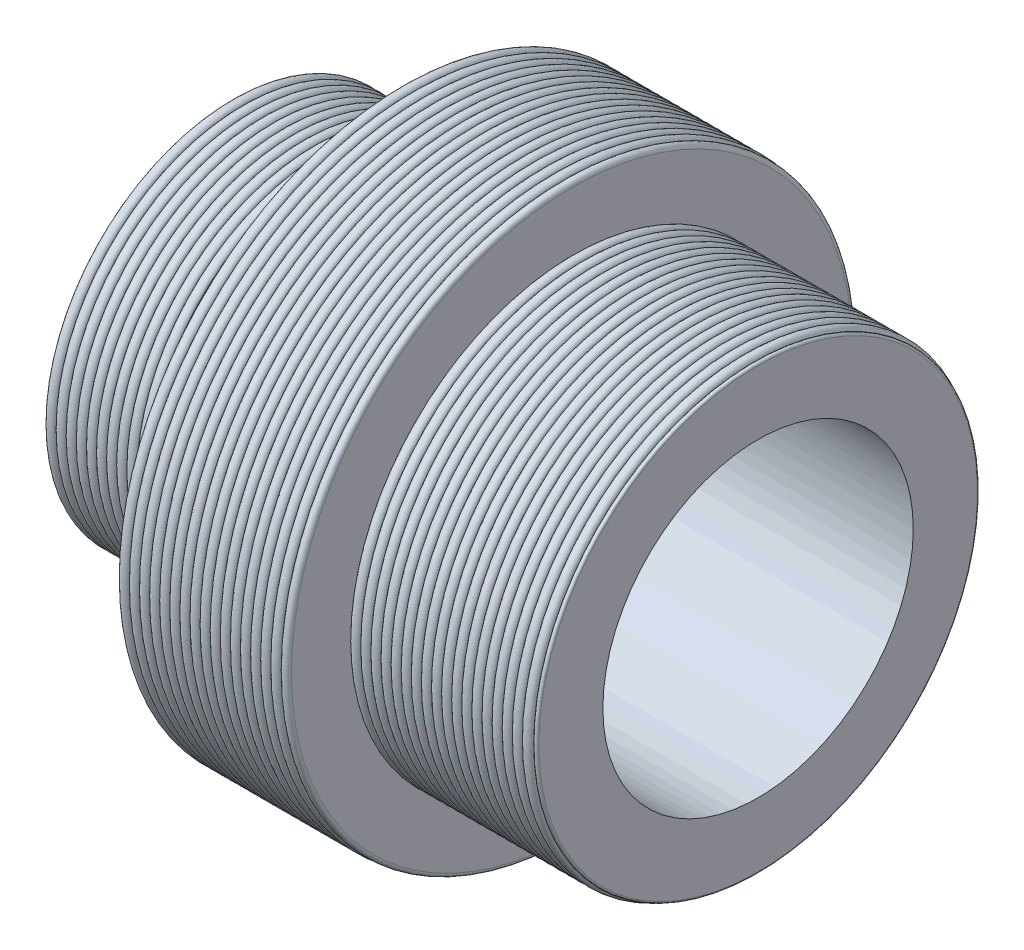
SolidWorks part; units mm, degrees
ref_plane "Alzado" through (0, 0, 0) normal (0, 0, 1) x (1, 0, 0)
ref_plane "Planta" through (0, 0, 0) normal (0, 1, 0) x (1, 0, 0)
ref_plane "Vista lateral" through (0, 0, 0) normal (1, 0, 0) x (0, 0, -1)
sketch "Croquis1" plane through (0, 0, 0) normal (0, 0, 1) x (1, 0, 0)
  line L0 (-55, 0) -> (55, 0) construction
  line L1 (0, 0) -> (0, 29.195) construction
  line L2 (48, 29.195) -> (13, 29.195)
  line L4 (13, 29.195) -> (-19, 29.195)
  line L5 (-19, 29.195) -> (-51, 29.195)
  line L6 (13, 29.195) -> (13, 52.78)
  line L7 (48, 29.195) -> (48, 41.245)
  line L8 (-19, 29.195) -> (-19, 52.78)
  line L9 (-51, 29.195) -> (-51, 34.565)
  line L11 (-51, 34.565) -> (-19, 34.565) construction
  line L12 (-19, 52.78) -> (13, 52.78) construction
  line L13 (13, 41.245) -> (48, 41.245) construction
  arc A0 (-51, 34.565) -> (-49.1, 34.565) centre (-50.05, 34.565) cw
  arc A1 (-49.1, 34.565) -> (-47.2, 34.565) centre (-48.15, 34.565) cw
  arc A2 (-47.2, 34.565) -> (-45.3, 34.565) centre (-46.25, 34.565) cw
  arc A3 (-45.3, 34.565) -> (-43.4, 34.565) centre (-44.35, 34.565) cw
  arc A4 (-43.4, 34.565) -> (-41.5, 34.565) centre (-42.45, 34.565) cw
  arc A5 (-41.5, 34.565) -> (-39.6, 34.565) centre (-40.55, 34.565) cw
  arc A6 (-39.6, 34.565) -> (-37.7, 34.565) centre (-38.65, 34.565) cw
  arc A7 (-37.7, 34.565) -> (-35.8, 34.565) centre (-36.75, 34.565) cw
  arc A8 (-35.8, 34.565) -> (-33.9, 34.565) centre (-34.85, 34.565) cw
  arc A9 (-33.9, 34.565) -> (-32, 34.565) centre (-32.95, 34.565) cw
  arc A10 (-32, 34.565) -> (-30.1, 34.565) centre (-31.05, 34.565) cw
  arc A11 (-30.1, 34.565) -> (-28.2, 34.565) centre (-29.15, 34.565) cw
  arc A12 (-28.2, 34.565) -> (-26.3, 34.565) centre (-27.25, 34.565) cw
  arc A13 (-26.3, 34.565) -> (-24.4, 34.565) centre (-25.35, 34.565) cw
  arc A14 (-24.4, 34.565) -> (-22.5, 34.565) centre (-23.45, 34.565) cw
  arc A15 (-22.5, 34.565) -> (-20.6, 34.565) centre (-21.55, 34.565) cw
  arc A16 (-20.6, 34.565) -> (-19, 34.565) centre (-19.8, 34.565) cw
  arc A17 (-19, 52.78) -> (-17.1, 52.78) centre (-18.05, 52.78) cw
  arc A18 (-17.1, 52.78) -> (-15.2, 52.78) centre (-16.15, 52.78) cw
  arc A19 (-15.2, 52.78) -> (-13.3, 52.78) centre (-14.25, 52.78) cw
  arc A20 (-13.3, 52.78) -> (-11.4, 52.78) centre (-12.35, 52.78) cw
  arc A21 (-11.4, 52.78) -> (-9.5, 52.78) centre (-10.45, 52.78) cw
  arc A22 (-9.5, 52.78) -> (-7.6, 52.78) centre (-8.55, 52.78) cw
  arc A23 (-7.6, 52.78) -> (-5.7, 52.78) centre (-6.65, 52.78) cw
  arc A24 (-5.7, 52.78) -> (-3.8, 52.78) centre (-4.75, 52.78) cw
  arc A25 (-3.8, 52.78) -> (-1.9, 52.78) centre (-2.85, 52.78) cw
  arc A26 (-1.9, 52.78) -> (0, 52.78) centre (-0.95, 52.78) cw
  arc A27 (0, 52.78) -> (1.9, 52.78) centre (0.95, 52.78) cw
  arc A28 (1.9, 52.78) -> (3.8, 52.78) centre (2.85, 52.78) cw
  arc A29 (3.8, 52.78) -> (5.7, 52.78) centre (4.75, 52.78) cw
  arc A30 (5.7, 52.78) -> (7.6, 52.78) centre (6.65, 52.78) cw
  arc A31 (7.6, 52.78) -> (9.5, 52.78) centre (8.55, 52.78) cw
  arc A32 (9.5, 52.78) -> (11.4, 52.78) centre (10.45, 52.78) cw
  arc A33 (11.4, 52.78) -> (13, 52.78) centre (12.2, 52.78) cw
  arc A34 (13, 41.245) -> (14.9, 41.245) centre (13.95, 41.245) cw
  arc A35 (14.9, 41.245) -> (16.8, 41.245) centre (15.85, 41.245) cw
  arc A36 (16.8, 41.245) -> (18.7, 41.245) centre (17.75, 41.245) cw
  arc A37 (18.7, 41.245) -> (20.6, 41.245) centre (19.65, 41.245) cw
  arc A38 (20.6, 41.245) -> (22.5, 41.245) centre (21.55, 41.245) cw
  arc A39 (22.5, 41.245) -> (24.4, 41.245) centre (23.45, 41.245) cw
  arc A40 (24.4, 41.245) -> (26.3, 41.245) centre (25.35, 41.245) cw
  arc A41 (26.3, 41.245) -> (28.2, 41.245) centre (27.25, 41.245) cw
  arc A42 (28.2, 41.245) -> (30.1, 41.245) centre (29.15, 41.245) cw
  arc A43 (30.1, 41.245) -> (32, 41.245) centre (31.05, 41.245) cw
  arc A44 (32, 41.245) -> (33.9, 41.245) centre (32.95, 41.245) cw
  arc A45 (33.9, 41.245) -> (35.8, 41.245) centre (34.85, 41.245) cw
  arc A46 (35.8, 41.245) -> (37.7, 41.245) centre (36.75, 41.245) cw
  arc A47 (37.7, 41.245) -> (39.6, 41.245) centre (38.65, 41.245) cw
  arc A48 (39.6, 41.245) -> (41.5, 41.245) centre (40.55, 41.245) cw
  arc A49 (41.5, 41.245) -> (43.4, 41.245) centre (42.45, 41.245) cw
  arc A50 (43.4, 41.245) -> (45.3, 41.245) centre (44.35, 41.245) cw
  arc A51 (45.3, 41.245) -> (47.2, 41.245) centre (46.25, 41.245) cw
  arc A52 (47.2, 41.245) -> (48, 41.245) centre (47.6, 41.245) cw
  point P4 (-48.15, 34.565)
  point P18 (-47.2, 34.565)
  point P19 (-46.25, 34.565)
  point P20 (-45.3, 34.565)
  point P21 (-44.35, 34.565)
  point P22 (-43.4, 34.565)
  point P23 (-42.45, 34.565)
  point P24 (-41.5, 34.565)
  point P25 (-40.55, 34.565)
  point P26 (-39.6, 34.565)
  point P27 (-38.65, 34.565)
  point P28 (-37.7, 34.565)
  point P29 (-36.75, 34.565)
  point P30 (-35.8, 34.565)
  point P31 (-34.85, 34.565)
  point P32 (-33.9, 34.565)
  point P33 (-32.95, 34.565)
  point P34 (-32, 34.565)
  point P35 (-31.05, 34.565)
  point P36 (-30.1, 34.565)
  point P37 (-29.15, 34.565)
  point P38 (-28.2, 34.565)
  point P39 (-27.25, 34.565)
  point P40 (-26.3, 34.565)
  point P41 (-25.35, 34.565)
  point P42 (-24.4, 34.565)
  point P43 (-23.45, 34.565)
  point P44 (-22.5, 34.565)
  point P45 (-21.55, 34.565)
  point P46 (-20.6, 34.565)
  point P47 (-19.8, 34.565)
  point P80 (-18.05, 52.78)
  point P81 (-17.1, 52.78)
  point P82 (-16.15, 52.78)
  point P83 (-15.2, 52.78)
  point P84 (-14.25, 52.78)
  point P85 (-13.3, 52.78)
  point P86 (-12.35, 52.78)
  point P87 (-11.4, 52.78)
  point P88 (-10.45, 52.78)
  point P89 (-9.5, 52.78)
  point P90 (-8.55, 52.78)
  point P91 (-7.6, 52.78)
  point P92 (-6.65, 52.78)
  point P93 (-5.7, 52.78)
  point P94 (-4.75, 52.78)
  point P95 (-3.8, 52.78)
  point P96 (-2.85, 52.78)
  point P97 (-1.9, 52.78)
  point P98 (-0.95, 52.78)
  point P99 (0, 52.78)
  point P100 (0.95, 52.78)
  point P101 (1.9, 52.78)
  point P102 (2.85, 52.78)
  point P103 (3.8, 52.78)
  point P104 (4.75, 52.78)
  point P105 (5.7, 52.78)
  point P106 (6.65, 52.78)
  point P107 (7.6, 52.78)
  point P108 (8.55, 52.78)
  point P109 (9.5, 52.78)
  point P110 (10.45, 52.78)
  point P111 (11.4, 52.78)
  point P112 (12.2, 52.78)
  point P147 (13.95, 41.245)
  point P148 (14.9, 41.245)
  point P149 (15.85, 41.245)
  point P150 (16.8, 41.245)
  point P151 (17.75, 41.245)
  point P152 (18.7, 41.245)
  point P153 (19.65, 41.245)
  point P154 (20.6, 41.245)
  point P155 (21.55, 41.245)
  point P156 (22.5, 41.245)
  point P157 (23.45, 41.245)
  point P158 (24.4, 41.245)
  point P159 (25.35, 41.245)
  point P160 (26.3, 41.245)
  point P161 (27.25, 41.245)
  point P162 (28.2, 41.245)
  point P163 (29.15, 41.245)
  point P164 (30.1, 41.245)
  point P166 (31.05, 41.245)
  point P167 (32, 41.245)
  point P168 (32.95, 41.245)
  point P169 (33.9, 41.245)
  point P171 (34.85, 41.245)
  point P172 (35.8, 41.245)
  point P174 (36.75, 41.245)
  point P175 (37.7, 41.245)
  point P177 (38.65, 41.245)
  point P178 (39.6, 41.245)
  point P179 (40.55, 41.245)
  point P181 (41.5, 41.245)
  point P183 (42.45, 41.245)
  point P184 (43.4, 41.245)
  point P185 (47.6, 41.245)
  point P186 (44.35, 41.245)
  point P187 (45.3, 41.245)
  point P188 (46.25, 41.245)
  point P190 (47.2, 41.245)
  dimension "D1" = 35
  dimension "D2" = 29.195
  dimension "D3" = 23.585
  dimension "D4" = 5.37
  dimension "D5" = 32
  dimension "D6" = 32
  dimension "D7" = 0.95
  dimension "D8" = 12.05
  dimension "D9" = 0.95
  dimension "D10" = 0.95
  dimension "D11" = 0.95
  dimension "D12" = 0.95
  dimension "D13" = 0.95
  dimension "D14" = 0.95
  dimension "D15" = 0.95
  dimension "D16" = 0.95
  dimension "D17" = 0.95
  dimension "D18" = 0.95
  dimension "D19" = 0.95
  dimension "D20" = 0.95
  dimension "D21" = 0.95
  dimension "D22" = 0.95
  dimension "D23" = 0.95
  dimension "D24" = 0.95
  dimension "D25" = 0.95
  dimension "D26" = 0.95
  dimension "D27" = 0.95
  dimension "D28" = 0.95
  dimension "D29" = 0.95
  dimension "D30" = 0.95
  dimension "D31" = 0.95
  dimension "D32" = 0.95
  dimension "D33" = 0.95
  dimension "D34" = 0.95
  dimension "D35" = 0.95
  dimension "D36" = 0.95
  dimension "D37" = 0.95
  dimension "D38" = 0.95
  dimension "D39" = 0.8
  dimension "D40" = 0.95
  dimension "D41" = 0.95
  dimension "D42" = 0.95
  dimension "D43" = 0.95
  dimension "D44" = 0.95
  dimension "D45" = 0.95
  dimension "D46" = 0.95
  dimension "D47" = 0.95
  dimension "D48" = 0.95
  dimension "D49" = 0.95
  dimension "D50" = 0.95
  dimension "D51" = 0.95
  dimension "D52" = 0.95
  dimension "D53" = 0.95
  dimension "D54" = 0.95
  dimension "D55" = 0.95
  dimension "D56" = 0.95
  dimension "D57" = 0.95
  dimension "D58" = 0.95
  dimension "D59" = 0.95
  dimension "D60" = 0.95
  dimension "D61" = 0.95
  dimension "D62" = 0.95
  dimension "D63" = 0.95
  dimension "D64" = 0.95
  dimension "D65" = 0.95
  dimension "D66" = 0.95
  dimension "D67" = 0.95
  dimension "D68" = 0.95
  dimension "D69" = 0.95
  dimension "D70" = 0.95
  dimension "D71" = 0.95
  dimension "D72" = 0.8
  dimension "D73" = 0.95
  dimension "D74" = 0.95
  dimension "D75" = 0.95
  dimension "D76" = 0.95
  dimension "D77" = 0.95
  dimension "D78" = 0.95
  dimension "D79" = 0.95
  dimension "D80" = 0.95
  dimension "D81" = 0.95
  dimension "D82" = 0.95
  dimension "D83" = 0.95
  dimension "D84" = 0.95
  dimension "D85" = 0.95
  dimension "D86" = 0.95
  dimension "D87" = 0.95
  dimension "D88" = 0.95
  dimension "D89" = 0.95
  dimension "D90" = 0.95
  dimension "D91" = 0.95
  dimension "D92" = 0.95
  dimension "D93" = 0.95
  dimension "D94" = 0.95
  dimension "D95" = 0.95
  dimension "D96" = 0.95
  dimension "D97" = 0.95
  dimension "D98" = 0.95
  dimension "D99" = 0.95
  dimension "D100" = 0.95
  dimension "D101" = 0.95
  dimension "D102" = 0.95
  dimension "D103" = 0.95
  dimension "D104" = 0.95
  dimension "D105" = 0.95
  dimension "D106" = 0.95
  dimension "D107" = 0.95
  dimension "D108" = 0.95
  dimension "D109" = 0.4
revolve "Revolución1" add sketch "Croquis1" angle 360 about L0
